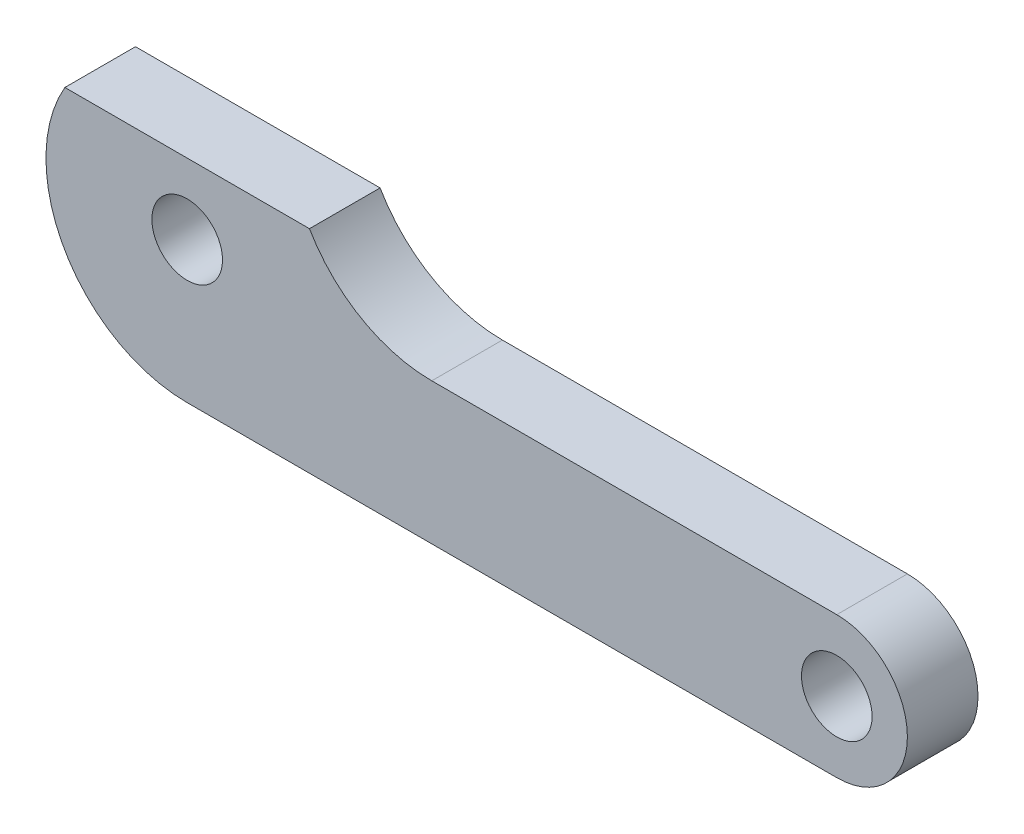
SolidWorks part; units mm, degrees
ref_plane "Plan de face" through (0, 0, 0) normal (0, 0, 1) x (1, 0, 0)
ref_plane "Plan de dessus" through (0, 0, 0) normal (0, 1, 0) x (1, 0, 0)
ref_plane "Plan de droite" through (0, 0, 0) normal (1, 0, 0) x (0, 0, -1)
sketch "Esquisse1" plane through (0, 0, 0) normal (0, 0, 1) x (1, 0, 0)
  line L0 (0, 0) -> (-46, 0)
  line L1 (0, 10) -> (-36, 10)
  arc A0 (0, 10) -> (0, 0) centre (0, 5) cw
  arc A1 (-46, 0) -> (-36, 10) centre (-46, 10) cw
  circle A2 centre (-46, 10) radius 2.5
  circle A3 centre (0, 5) radius 2.5
  point P6 (-46, 10)
  dimension "D2" = 10
  dimension "D3" = 5
  dimension "D4" = 5
  dimension "D5" = 5
  dimension "D1" = 46
extrude "Boss.-Extru.1" add sketch "Esquisse1" along normal blind 5
fillet "Congé1" radius 10 1 edges at (-36, 10, 2.5)
sketch "Esquisse2" plane through (0, 0, 5) normal (0, 0, 1) x (1, 0, 0)
  line L1 (-56, 20) -> (-37.3397, 20)
  line L2 (-56, 20) -> (-56, 15)
  line L3 (-56, 15) -> (-37.3397, 15)
  line L4 (-37.3397, 20) -> (-37.3397, 15)
  arc A0 (-37.3397, 15) -> (-46, 0) centre (-46, 10) ccw construction
extrude "Enlèv. mat.-Extru.1" cut sketch "Esquisse2" against normal blind 5
